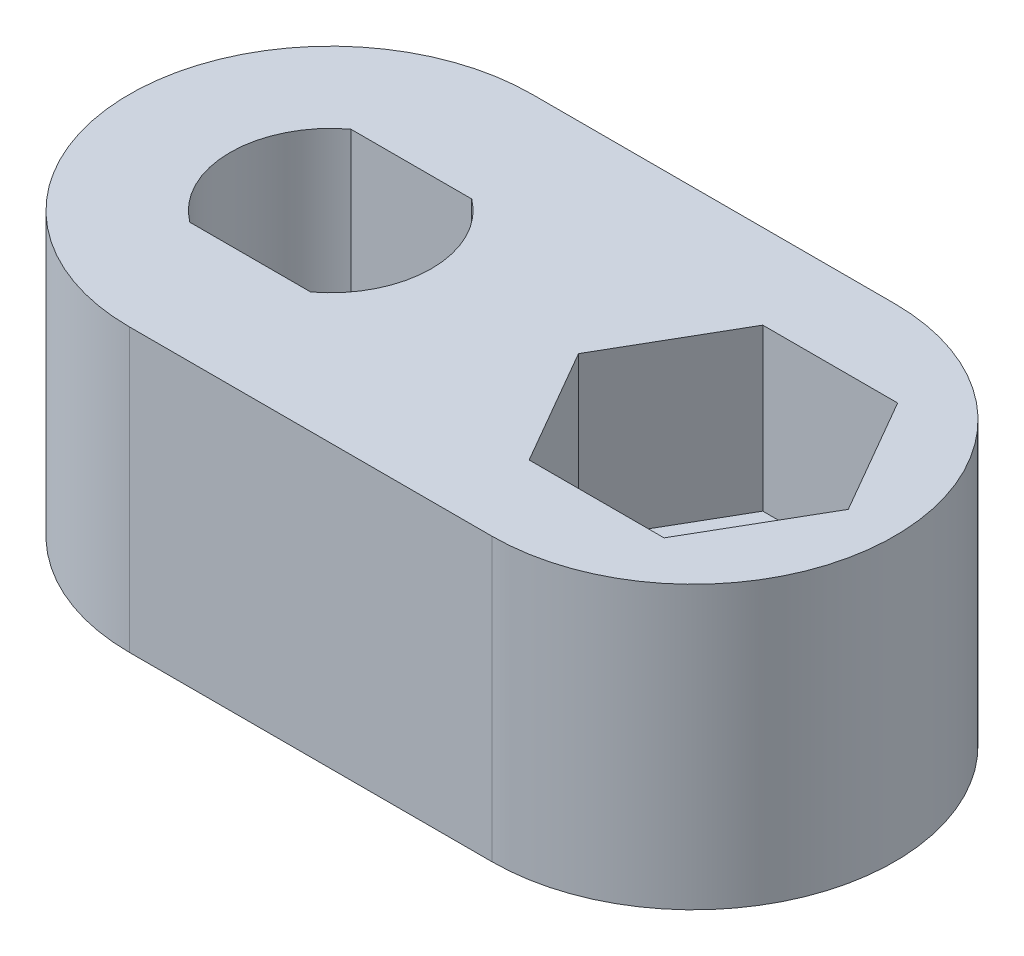
SolidWorks part; units mm, degrees
ref_plane "前视基准面" through (0, 0, 0) normal (0, 0, 1) x (1, 0, 0)
ref_plane "上视基准面" through (0, 0, 0) normal (0, 1, 0) x (1, 0, 0)
ref_plane "右视基准面" through (0, 0, 0) normal (1, 0, 0) x (0, 0, -1)
sketch "草图1" plane through (0, 0, 0) normal (0, 1, 0) x (1, 0, 0)
  line L0 (-4.5, 0) -> (4.5, 0) construction
  line L1 (-4.5, 5) -> (4.5, 5)
  line L2 (-4.5, -5) -> (4.5, -5)
  arc A0 (-4.5, 5) -> (-4.5, -5) centre (-4.5, 0) ccw
  arc A1 (4.5, -5) -> (4.5, 5) centre (4.5, 0) ccw
  point P2 (0, 0)
  dimension "D1" = 10
  dimension "D2" = 9
extrude "凸台-拉伸1" add sketch "草图1" along normal blind 7
sketch "草图2" plane through (0, 7, 0) normal (0, 1, 0) x (1, 0, 0)
  line L0 (0, 0) -> (-9.1692, 0) construction
  line L1 (-6, 2) -> (-3, 2)
  line L2 (-6, -2) -> (-3, -2)
  circle A0 centre (-4.5, 0) radius 2.5
  point P8 (-4.5, 0)
  dimension "D2" = 5
  dimension "D1" = 4
extrude "切除-拉伸1" cut sketch "草图2" against normal blind 4
hole_wizard "M3 六角凹锥坑螺钉的锥形沉头孔1" positions "草图8" profile "草图9" countersink size "M3" standard "ISO"
sketch "草图8" plane through (0, 0, 0) normal (0, -1, 0) x (-1, 0, 0)
  point P0 (4.5, 0)
sketch "草图9" plane through (-4.5, 0, 0) normal (1, 0, 0) x (0, 0, -1)
  line L0 (0, 0) -> (0, 8.5215)
  line L1 (0, 8.5215) -> (1.7, 7.5)
  line L2 (1.7, 7.5) -> (1.7, 1.66)
  line L3 (1.7, 1.66) -> (3.36, 0)
  line L5 (3.36, 0) -> (0, 0)
  line L6 (-1.7, 1.66) -> (-3.36, 0) construction
  line L10 (0, 8.5215) -> (-1.7, 7.5) construction
  line L11 (0, -6.35) -> (0, 107.95) construction
  dimension "孔直径" = 3.4
  dimension "孔深度" = 7.5
  dimension "近端锥形沉头孔直径" = 6.72
  dimension "近端锥形沉头孔角度" = 90
  dimension "导头角度" = 118
hole_wizard "孔1" positions "草图10" profile "草图11" legacy end condition through all
sketch "草图10" plane through (0, 7, 0) normal (0, 1, 0) x (1, 0, 0)
  point P2 (5, 0)
  point P5 (0, 0)
sketch "草图11" plane through (5, 7, 0) normal (1, 0, 0) x (0, 0, 1)
  line L0 (0, 0) -> (0, 7)
  line L1 (0, 7) -> (2.075, 7)
  line L2 (2.075, 7) -> (2.075, 0)
  line L3 (2.075, 0) -> (0, 0)
  line L4 (0, 110) -> (0, -10) construction
  dimension "直径" = 4.15
  dimension "深度" = 7
sketch "草图12" plane through (0, 7, 0) normal (0, 1, 0) x (1, 0, 0)
  line L0 (4.5, 5) -> (-4.5, 5) construction
  line L1 (8.3486, 0) -> (6.6743, 2.9)
  line L2 (6.6743, 2.9) -> (3.3257, 2.9)
  line L3 (3.3257, 2.9) -> (1.6514, 0)
  line L4 (1.6514, 0) -> (3.3257, -2.9)
  line L5 (3.3257, -2.9) -> (6.6743, -2.9)
  line L6 (6.6743, -2.9) -> (8.3486, 0)
  circle A0 centre (5, 0) radius 2.9 construction
  point P11 (5, -0.4368)
  point P12 (0, 0)
  point P13 (5, 0)
  dimension "D1" = 5.8
extrude "切除-拉伸2" cut sketch "草图12" against normal blind 4
